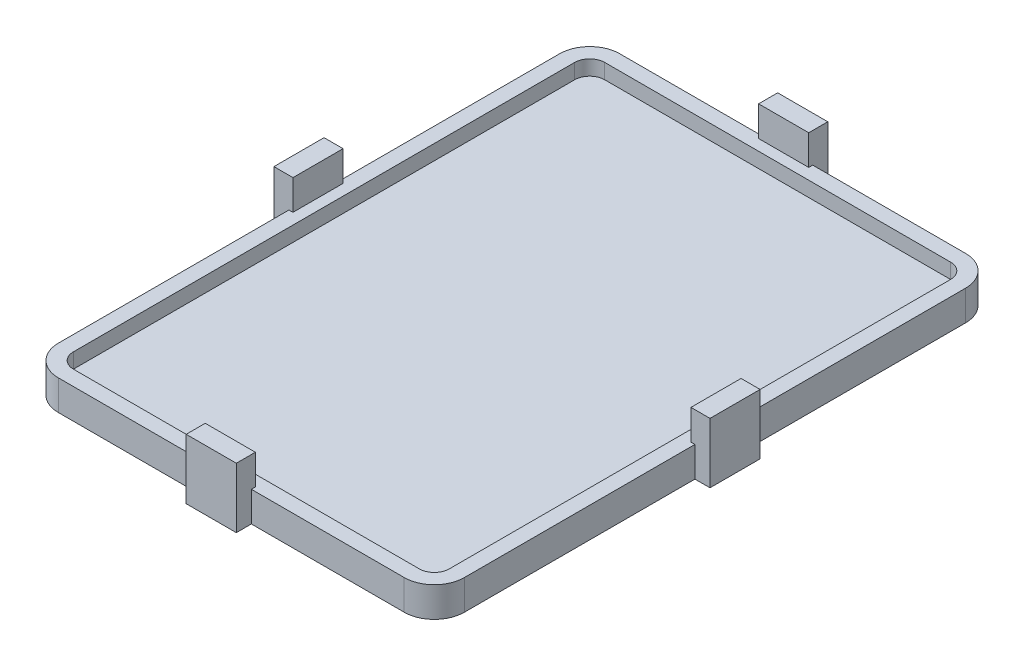
SolidWorks part; units mm, degrees
ref_plane "Front Plane" through (0, 0, 0) normal (0, 0, 1) x (1, 0, 0)
ref_plane "Top Plane" through (0, 0, 0) normal (0, 1, 0) x (1, 0, 0)
ref_plane "Right Plane" through (0, 0, 0) normal (1, 0, 0) x (0, 0, -1)
sketch "Sketch1" plane through (0, 0, 0) normal (0, 1, 0) x (1, 0, 0)
  line L1 (0, 0) -> (40.5, 0)
  line L2 (0, 0) -> (0, 56)
  line L3 (0, 56) -> (40.5, 56)
  line L4 (40.5, 0) -> (40.5, 56)
  dimension "D1" = 40.5
  dimension "D2" = 56
extrude "Boss-Extrude1" add sketch "Sketch1" along normal blind 3
fillet "Fillet1" radius 3 4 edges at (0, 1.5, 0) (40.5, 1.5, 0) (40.5, 1.5, -56) (0, 1.5, -56)
shell "Shell1" thickness 1.5
sketch "Sketch2" plane through (0, 0, 0) normal (-1, 0, 0) x (0, 0, 1)
  line L0 (-53, 0) -> (-3, 0) construction
  line L1 (-31, 3) -> (-26, 3)
  line L2 (-31, 3) -> (-31, 0)
  line L3 (-31, 0) -> (-26, 0)
  line L4 (-26, 3) -> (-26, 0)
  line L5 (-56, 0) -> (-56, 3) construction
  point P6 (-56, 1.5)
  dimension "D1" = 5
  dimension "D2" = 3
  dimension "D3" = 0
  dimension "D4" = 25
extrude "Boss-Extrude2" add sketch "Sketch2" along normal blind 1.5
sketch "Sketch3" plane through (0, 3, 0) normal (0, 1, 0) x (1, 0, 0)
  line L0 (-1.5, 26) -> (-1.5, 31) construction
  line L1 (0.4, 31) -> (-1.5, 31)
  line L2 (0.4, 31) -> (0.4, 26)
  line L3 (0.4, 26) -> (-1.5, 26)
  line L4 (-1.5, 31) -> (-1.5, 26)
  line L5 (-1.5, 26) -> (0, 26) construction
  point P4 (-1.5, 28.5)
  dimension "D1" = 5
  dimension "D2" = 1.9
  dimension "D3" = 0
  dimension "D4" = 0
extrude "Boss-Extrude3" add sketch "Sketch3" along normal blind 3
ref_plane "Plane2" through (20.25, 0, 0) normal (1, 0, 0) x (0, 0, -1)
sketch "Sketch8" plane through (0, 0, 0) normal (0, 0, 1) x (1, 0, 0)
  line L0 (3, 0) -> (37.5, 0) construction
  line L1 (17.25, 3) -> (22.25, 3)
  line L2 (17.25, 3) -> (17.25, 0)
  line L3 (17.25, 0) -> (22.25, 0)
  line L4 (22.25, 3) -> (22.25, 0)
  line L5 (0, 0) -> (0, 3) construction
  dimension "D1" = 5
  dimension "D2" = 3
  dimension "D3" = 0
  dimension "D4" = 17.25
extrude "Boss-Extrude5" add sketch "Sketch8" along normal blind 1.5
sketch "Sketch9" plane through (0, 3, 0) normal (0, 1, 0) x (1, 0, 0)
  line L0 (22.25, -1.5) -> (17.25, -1.5) construction
  line L1 (17.25, 0.4) -> (22.25, 0.4)
  line L2 (17.25, 0.4) -> (17.25, -1.5)
  line L3 (17.25, -1.5) -> (22.25, -1.5)
  line L4 (22.25, 0.4) -> (22.25, -1.5)
  line L5 (22.25, -1.5) -> (22.25, 0) construction
  dimension "D1" = 1.9
  dimension "D2" = 5
  dimension "D3" = 0
  dimension "D4" = 0
extrude "Boss-Extrude6" add sketch "Sketch9" along normal blind 3
ref_plane "Plane3" through (0, 0, -28) normal (0, 0, -1) x (-1, 0, 0)
mirror "Mirror3" about plane through (20.25, 0, 0) normal (1, 0, 0) of "Boss-Extrude3", "Boss-Extrude2"
mirror "Mirror4" about plane through (0, 0, -28) normal (0, 0, -1) of "Boss-Extrude6", "Boss-Extrude5"
